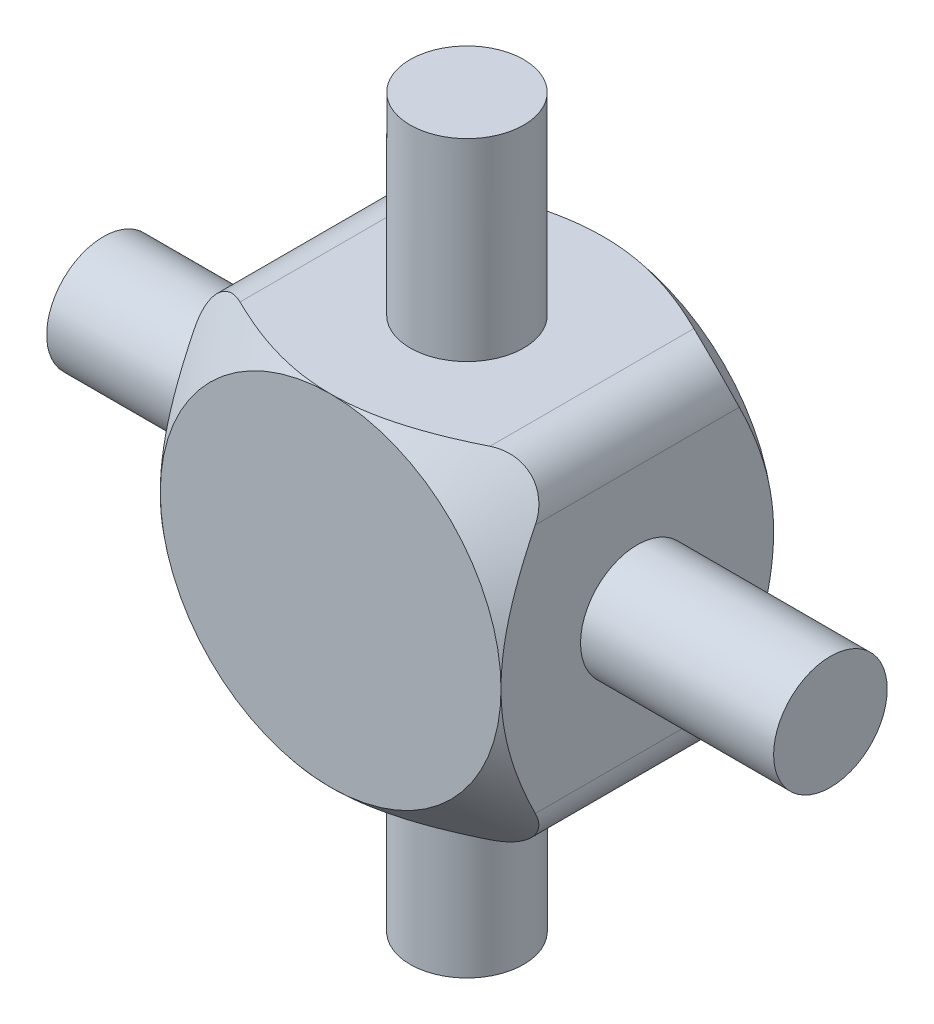
SolidWorks part; units mm, degrees
material "Brass"
ref_plane "Front Plane" through (0, 0, 0) normal (0, 0, 1) x (1, 0, 0)
ref_plane "Top Plane" through (0, 0, 0) normal (0, 1, 0) x (1, 0, 0)
ref_plane "Right Plane" through (0, 0, 0) normal (1, 0, 0) x (0, 0, -1)
sketch "Sketch1" plane through (0, 0, 0) normal (0, 0, 1) x (1, 0, 0)
  line L1 (-7.5, -7.5) -> (7.5, -7.5)
  line L2 (-7.5, -7.5) -> (-7.5, 7.5)
  line L3 (-7.5, 7.5) -> (7.5, 7.5)
  line L4 (7.5, -7.5) -> (7.5, 7.5)
  line L5 (-7.5, -7.5) -> (7.5, 7.5) construction
  line L6 (-7.5, 7.5) -> (7.5, -7.5) construction
  point P0 (0, 0)
  dimension "D1" = 15
  dimension "D2" = 15
extrude "Boss-Extrude1" add sketch "Sketch1" along normal blind 12
sketch "Sketch2" plane through (0, 0, 12) normal (0, 0, 1) x (1, 0, 0)
  line L0 (7.5, 7.5) -> (-7.5, 7.5) construction
  circle A0 centre (0, 0) radius 7.5
extrude "Cut-Extrude1" cut sketch "Sketch2" against normal blind 20 draft 50 flip side to cut
sketch "Sketch3" plane through (0, 0, 0) normal (0, 0, -1) x (-1, 0, 0)
  line L0 (-7.5, 7.5) -> (7.5, 7.5) construction
  circle A0 centre (0, 0) radius 7.5
extrude "Cut-Extrude2" cut sketch "Sketch3" against normal blind 20 draft 50 flip side to cut
fillet "Fillet1" radius 2 4 edges at (7.5, -7.5, 6) (7.5, 7.5, 6) (-7.5, 7.5, 6) (-7.5, -7.5, 6)
sketch "Sketch5" plane through (0, 0, 0) normal (0, 1, 0) x (1, 0, 0)
  circle A0 centre (0, -6) radius 2.5
  dimension "D1" = 5
  dimension "D2" = 6
extrude "Boss-Extrude2" add sketch "Sketch5" along normal mid plane 32
sketch "Sketch6" plane through (0, 0, 0) normal (1, 0, 0) x (0, 0, -1)
  circle A0 centre (-6, 0) radius 2.5
  dimension "D1" = 5
  dimension "D2" = 6
extrude "Boss-Extrude3" add sketch "Sketch6" along normal mid plane 32
